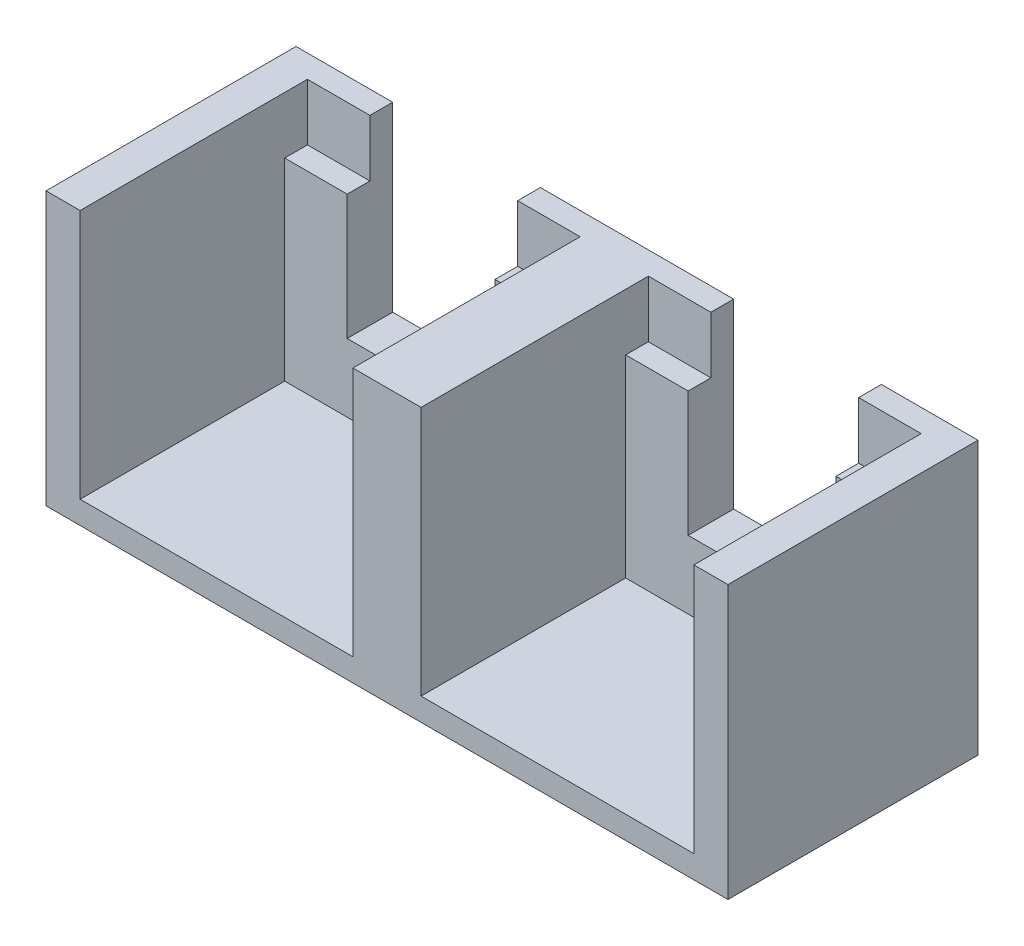
SolidWorks part; units mm, degrees
ref_plane "正面" through (0, 0, 0) normal (0, 0, 1) x (1, 0, 0)
ref_plane "平面" through (0, 0, 0) normal (0, 1, 0) x (1, 0, 0)
ref_plane "右側面" through (0, 0, 0) normal (1, 0, 0) x (0, 0, -1)
sketch "ｽｹｯﾁ1" plane through (0, 0, 0) normal (0, 0, 1) x (1, 0, 0)
  line L1 (-30, -12) -> (30, -12)
  line L2 (-30, -12) -> (-30, 12)
  line L3 (-30, 12) -> (30, 12)
  line L4 (30, -12) -> (30, 12)
  line L5 (-30, -12) -> (30, 12) construction
  line L6 (-30, 12) -> (30, -12) construction
  point P0 (0, 0)
  dimension "D1" = 24
  dimension "D2" = 60
extrude "ﾎﾞｽ - 押し出し1" add sketch "ｽｹｯﾁ1" along normal blind 22
sketch "ｽｹｯﾁ3" plane through (0, 0, 22) normal (0, 0, 1) x (1, 0, 0)
  line L1 (-27, -10) -> (-3, -10)
  line L2 (-27, -10) -> (-27, 10)
  line L3 (-27, 10) -> (-3, 10)
  line L4 (-3, -10) -> (-3, 10)
  line L5 (-27, -10) -> (-3, 10) construction
  line L6 (-27, 10) -> (-3, -10) construction
  point P0 (-15, 0)
  dimension "D1" = 20
  dimension "D2" = 24
  dimension "D3" = 15
extrude "ｶｯﾄ - 押し出し2" cut sketch "ｽｹｯﾁ3" against normal blind 18
sketch "ｽｹｯﾁ5" plane through (0, 0, 4) normal (0, 0, 1) x (1, 0, 0)
  line L1 (-21.5, 12) -> (-8.5, 12)
  line L2 (-21.5, 12) -> (-21.5, -4)
  line L3 (-21.5, -4) -> (-8.5, -4)
  line L4 (-8.5, 12) -> (-8.5, -4)
  line L5 (30, 12) -> (-30, 12) construction
  line L6 (-27, -10) -> (-3, -10) construction
  point P4 (-15, -4)
  point P9 (-15, -10)
  dimension "D1" = 0
  dimension "D2" = 6
  dimension "D3" = 13
extrude "ｶｯﾄ - 押し出し4" cut sketch "ｽｹｯﾁ5" against normal up to surface (4 mm away) up to face at (0, 0, 0)
sketch "ｽｹｯﾁ6" plane through (0, 12, 0) normal (0, 1, 0) x (1, 0, 0)
  line L0 (-21.5, 0) -> (-30, 0) construction
  line L1 (-27, -2) -> (-3, -2)
  line L2 (-27, -2) -> (-27, -22)
  line L3 (-27, -22) -> (-3, -22)
  line L4 (-3, -2) -> (-3, -22)
  line L7 (30, -22) -> (-30, -22) construction
  line L8 (-27, -4) -> (-27, -22) construction
  line L9 (-3, -4) -> (-3, -22) construction
  dimension "D1" = 2
extrude "ｶｯﾄ - 押し出し5" cut sketch "ｽｹｯﾁ6" against normal blind 5
mirror "ﾐﾗｰ1" about plane through (0, 0, 0) normal (1, 0, 0) of "ｶｯﾄ - 押し出し5", "ｶｯﾄ - 押し出し2", "ｶｯﾄ - 押し出し4"
